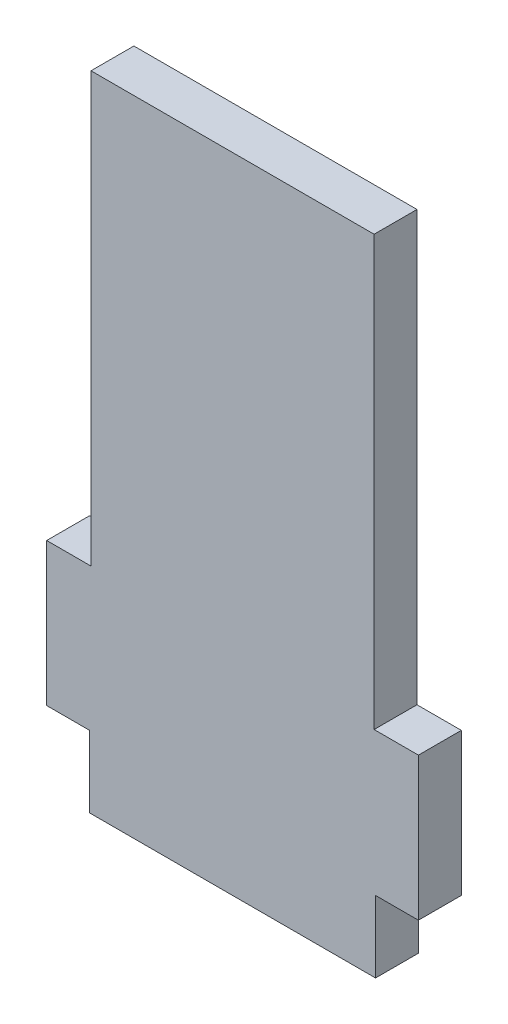
SolidWorks part; units mm, degrees
ref_plane "Front Plane" through (0, 0, 0) normal (0, 0, 1) x (1, 0, 0)
ref_plane "Top Plane" through (0, 0, 0) normal (0, 1, 0) x (1, 0, 0)
ref_plane "Right Plane" through (0, 0, 0) normal (1, 0, 0) x (0, 0, -1)
sketch "Sketch2" plane through (0, 0, 0) normal (0, 1, 0) x (1, 0, 0)
  line L1 (-13, -1.5) -> (13, -1.5)
  line L2 (-13, -1.5) -> (-13, 1.5)
  line L3 (-13, 1.5) -> (13, 1.5)
  line L4 (13, -1.5) -> (13, 1.5)
  line L5 (0, 1.5) -> (0, -1.5) construction
  line L6 (-13, 0) -> (13, 0) construction
  point P0 (0, 0)
  dimension "D1" = 3
  dimension "D2" = 26
extrude "Boss-Extrude1" add sketch "Sketch2" along normal blind 10
sketch "Sketch4" plane through (0, 10, 0) normal (0, 1, 0) x (1, 0, 0)
  line L0 (13, 1.5) -> (-13, 1.5) construction
  line L1 (-9.9, -1.5) -> (9.9, -1.5)
  line L2 (-9.9, -1.5) -> (-9.9, 1.5)
  line L3 (-9.9, 1.5) -> (9.9, 1.5)
  line L4 (9.9, -1.5) -> (9.9, 1.5)
  line L5 (0, 1.5) -> (0, -1.5) construction
  line L6 (-9.9, 0) -> (9.9, 0) construction
  point P0 (0, 0)
  dimension "D1" = 3
  dimension "D2" = 19.8
extrude "Boss-Extrude2" add sketch "Sketch4" along normal blind 30
sketch "Sketch5" plane through (0, 0, 0) normal (0, -1, 0) x (1, 0, 0)
  line L0 (-13, 1.5) -> (13, 1.5) construction
  line L1 (-10, -1.5) -> (10, -1.5)
  line L2 (-10, -1.5) -> (-10, 1.5)
  line L3 (-10, 1.5) -> (10, 1.5)
  line L4 (10, -1.5) -> (10, 1.5)
  line L5 (0, 1.5) -> (0, -1.5) construction
  line L6 (-10, 0) -> (10, 0) construction
  point P0 (0, 0)
  dimension "D1" = 20
extrude "Boss-Extrude3" add sketch "Sketch5" along normal blind 5
